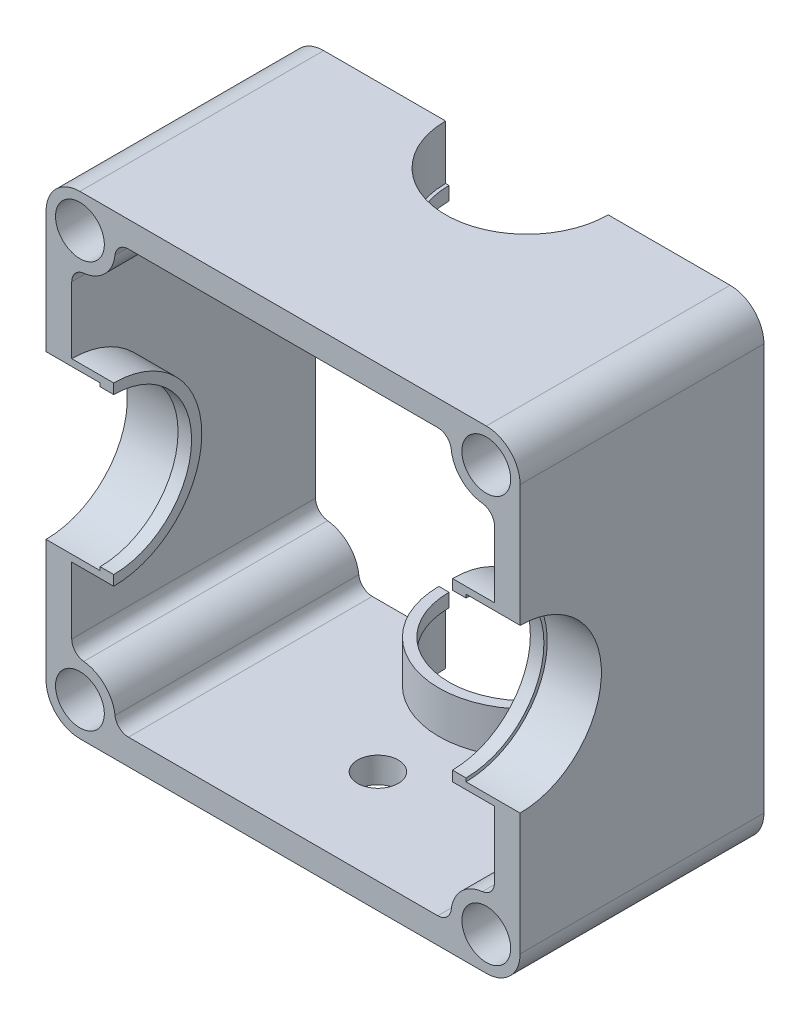
SolidWorks part; units mm, degrees
ref_plane "前视基准面" through (0, 0, 0) normal (0, 0, 1) x (1, 0, 0)
ref_plane "上视基准面" through (0, 0, 0) normal (0, 1, 0) x (1, 0, 0)
ref_plane "右视基准面" through (0, 0, 0) normal (1, 0, 0) x (0, 0, -1)
other "Configuration Table"
sketch "草图1" plane through (0, 0, 0) normal (0, 0, 1) x (-1, 0, 0)
  line L8 (-17.5, 15) -> (-17.5, -15)
  line L9 (-15, -17.5) -> (15, -17.5)
  line L10 (17.5, -15) -> (17.5, 15)
  line L11 (15, 17.5) -> (-15, 17.5)
  line L16 (15.6047, -11.417) -> (15.6047, 11.417)
  line L17 (-11.417, -15.6047) -> (11.417, -15.6047)
  line L18 (-15.6047, 11.417) -> (-15.6047, -11.417)
  line L19 (11.417, 15.6047) -> (-11.417, 15.6047)
  circle A2 centre (-15, -15) radius 1.8
  arc A8 (-15, 17.5) -> (-17.5, 15) centre (-15, 15) ccw
  arc A9 (-17.5, -15) -> (-15, -17.5) centre (-15, -15) ccw
  arc A10 (15, -17.5) -> (17.5, -15) centre (15, -15) ccw
  arc A11 (17.5, 15) -> (15, 17.5) centre (15, 15) ccw
  circle A12 centre (15, -15) radius 1.8
  circle A14 centre (15, 15) radius 1.8
  circle A16 centre (-15, 15) radius 1.8
  arc A38 (12.411, 14.7144) -> (14.7144, 12.411) centre (15, 15) ccw
  arc A39 (15.6047, 11.417) -> (14.7144, 12.411) centre (14.6048, 11.4171) ccw
  arc A40 (14.7144, -12.411) -> (15.6047, -11.417) centre (14.6048, -11.4171) ccw
  arc A41 (14.7144, -12.411) -> (12.411, -14.7144) centre (15, -15) ccw
  arc A42 (11.417, -15.6047) -> (12.411, -14.7144) centre (11.4171, -14.6048) ccw
  arc A43 (-12.411, -14.7144) -> (-11.417, -15.6047) centre (-11.4171, -14.6048) ccw
  arc A44 (-12.411, -14.7144) -> (-14.7144, -12.411) centre (-15, -15) ccw
  arc A45 (-15.6047, -11.417) -> (-14.7144, -12.411) centre (-14.6048, -11.4171) ccw
  arc A46 (-14.7144, 12.411) -> (-15.6047, 11.417) centre (-14.6048, 11.4171) ccw
  arc A47 (-14.7144, 12.411) -> (-12.411, 14.7144) centre (-15, 15) ccw
  arc A48 (-11.417, 15.6047) -> (-12.411, 14.7144) centre (-11.4171, 14.6048) ccw
  arc A49 (12.411, 14.7144) -> (11.417, 15.6047) centre (11.4171, 14.6048) ccw
extrude "凸台-拉伸1" add sketch "草图1" along normal blind 42
sketch "草图2" plane through (0, 17.5, 0) normal (0, 1, 0) x (1, 0, 0)
  line L0 (0, 0) -> (0, -12)
  circle A0 centre (0, -12) radius 6
  dimension "D2" = 12
  dimension "D1" = 12
extrude "切除-拉伸1" cut sketch "草图2" against normal through all
sketch "草图3" plane through (-17.5, 0, 0) normal (-1, 0, 0) x (0, 0, 1)
  line L0 (0, 0) -> (30, 0)
  circle A0 centre (30, 0) radius 6
  dimension "D2" = 12
  dimension "D1" = 30
extrude "切除-拉伸2" cut sketch "草图3" against normal through all
sketch "草图5" plane through (17.5, 0, 0) normal (1, 0, 0) x (0, 0, -1)
  line L0 (0, 0) -> (-12, 0)
  line L1 (-12, 0) -> (-12, -24.9743)
  line L3 (-30, 0) -> (-30, -24.9743)
  line L5 (-30, 0) -> (-30, 23.8795)
  line L7 (-12, 23.8795) -> (-12, 0)
  line L8 (-12, -24.9743) -> (12.1166, -24.9743)
  line L9 (12.1166, -24.9743) -> (12.1166, 23.8795)
  line L10 (12.1166, 23.8795) -> (-12, 23.8795)
  line L11 (-30, -24.9743) -> (-47.4121, -24.9743)
  line L12 (-47.4121, -24.9743) -> (-47.4121, 25.2382)
  line L13 (-47.4121, 25.2382) -> (-30, 23.8795)
  circle M15 centre (-30, 0) radius 6
  line M16 (0, -15) -> (0, 15)
  line M17 (0, 15) -> (-42, 15)
  line M18 (-42, 15) -> (-42, -15)
  line M19 (-42, -15) -> (0, -15)
  dimension "D1" = 12
extrude "切除-拉伸3" cut sketch "草图5" against normal through all contours L13 L12 L11 L3 L5 M19 M18 M17 | L5 L3 M15 M17 M18 M19 | L7 L0 M17 M16 | L9 L10 L7 L1 L8 M17 M16 M19 | L0 L1 M19 M16
sketch "草图6" plane through (0, 15.6047, 0) normal (0, -1, 0) x (-1, 0, 0)
  line L0 (-6, -12) -> (-6.5, -12)
  line L1 (6, -12) -> (6.5, -12)
  arc A0 (-6, -12) -> (6, -12) centre (0, -12) ccw
  arc A1 (-6.5, -12) -> (6.5, -12) centre (0, -12) ccw
  dimension "D1" = 12
  dimension "D2" = 13
extrude "凸台-拉伸2" add sketch "草图6" along normal blind 2.1
sketch "草图7" plane through (0, 13.5047, 0) normal (0, -1, 0) x (-1, 0, 0)
  line L0 (-6.5, -12) -> (-5.75, -12)
  line L1 (5.75, -12) -> (6.5, -12)
  arc A0 (-6.5, -12) -> (6.5, -12) centre (0, -12) ccw
  arc A1 (-5.75, -12) -> (5.75, -12) centre (0, -12) ccw
  dimension "D1" = 13
  dimension "D2" = 11.5
extrude "凸台-拉伸3" add sketch "草图7" along normal blind 1
ref_plane "基准面1" through (0, 0, 0) normal (0, -1, 0) x (-1, 0, 0)
mirror "镜向1" about plane through (0, 0, 0) normal (0, -1, 0) of "凸台-拉伸2", "凸台-拉伸3"
sketch "草图8" plane through (15.6047, 0, 0) normal (-1, 0, 0) x (0, 0, 1)
  line L0 (30, -6.5) -> (30, -6)
  line L2 (30, 6) -> (30, 6.5)
  arc A0 (30, 6) -> (30, -6) centre (30, 0) ccw
  arc A1 (30, 6.5) -> (30, -6.5) centre (30, 0) ccw
  dimension "D2" = 13
extrude "凸台-拉伸4" add sketch "草图8" along normal blind 2.1
sketch "草图9" plane through (13.5047, 0, 0) normal (-1, 0, 0) x (0, 0, 1)
  line L0 (30, -6.5) -> (30, -5.75)
  line L2 (30, 5.75) -> (30, 6.5)
  arc A0 (30, 6.5) -> (30, -6.5) centre (30, 0) ccw
  arc A1 (30, 5.75) -> (30, -5.75) centre (30, 0) ccw
  dimension "D1" = 13
  dimension "D2" = 11.5
extrude "凸台-拉伸5" add sketch "草图9" along normal blind 1
ref_plane "基准面2" through (0, 0, 0) normal (-1, 0, 0) x (0, 0, 1)
mirror "镜向2" about plane through (0, 0, 0) normal (-1, 0, 0) of "凸台-拉伸4", "凸台-拉伸5"
sketch "草图10" plane through (0, -17.5, 0) normal (0, -1, 0) x (1, 0, 0)
  circle A0 centre (0, 23) radius 1.5
extrude "切除-拉伸4" cut sketch "草图10" against normal blind 3
